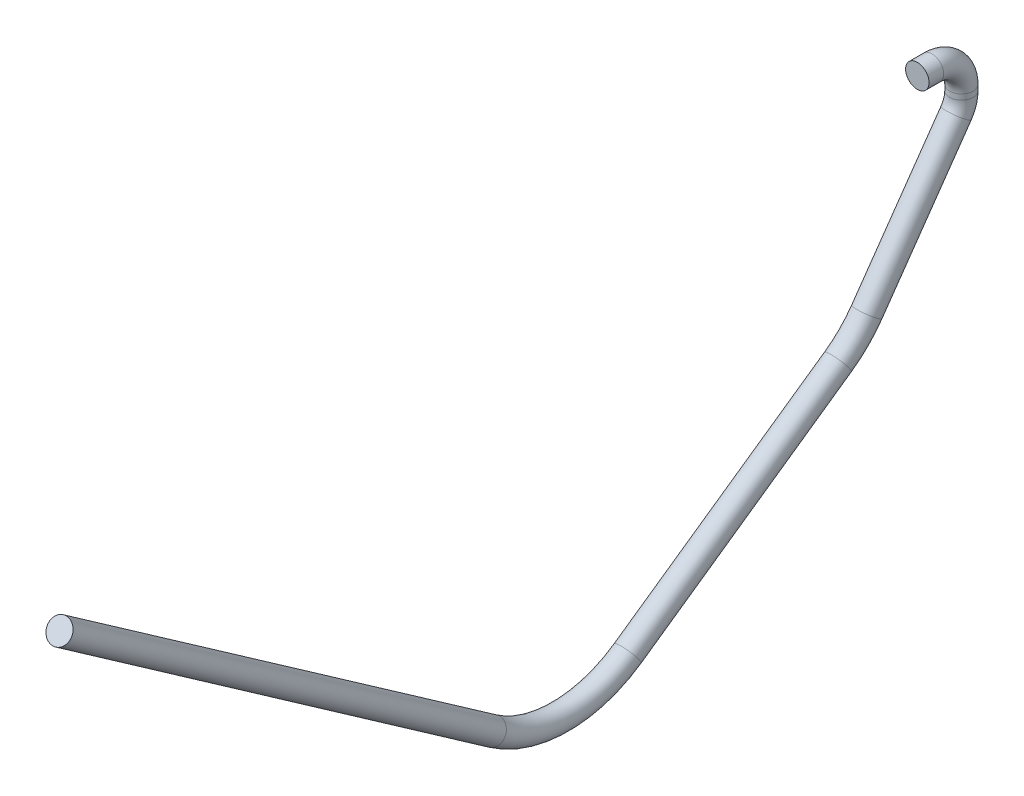
SolidWorks part; units mm, degrees
ref_plane "前视基准面" through (0, 0, 0) normal (0, 0, 1) x (1, 0, 0)
ref_plane "上视基准面" through (0, 0, 0) normal (0, 1, 0) x (1, 0, 0)
ref_plane "右视基准面" through (0, 0, 0) normal (1, 0, 0) x (0, 0, -1)
sketch "草图1" plane through (0, 0, 0) normal (0, 0, 1) x (1, 0, 0)
  circle A0 centre (0, 0) radius 4
  dimension "D1" = 8
sketch "草图2" plane through (0, 0, 0) normal (1, 0, 0) x (0, 0, -1)
  line L0 (0, 0) -> (5, 0)
  line L1 (15, -10) -> (15, -11.847)
  line L2 (13.1915, -17.5828) -> (-17.1776, -60.9544)
  line L3 (-27.0006, -70.7774) -> (-98.5282, -120.8615)
  line L4 (-144.4143, -120.8615) -> (-291.8617, -17.6178)
  arc A0 (15, -11.847) -> (13.1915, -17.5828) centre (5, -11.847) cw
  arc A1 (5, 0) -> (15, -10) centre (5, -10) cw
  arc A2 (-98.5282, -120.8615) -> (-144.4143, -120.8615) centre (-121.4713, -88.0955) cw
  arc A3 (-17.1776, -60.9544) -> (-27.0006, -70.7774) centre (-49.9437, -38.0113) cw
  point P7 (15, -15)
  point P10 (15, 0)
  point P17 (-21.2231, -66.7319)
  dimension "D4" = 10
  dimension "D6" = 20
  dimension "D8" = 40
  dimension "D1" = 35
  dimension "D2" = 15
  dimension "D3" = 15
  dimension "D5" = 60
  dimension "D7" = 115
  dimension "D9" = 180
sweep "扫描1" add profiles "草图1" path "草图2"
